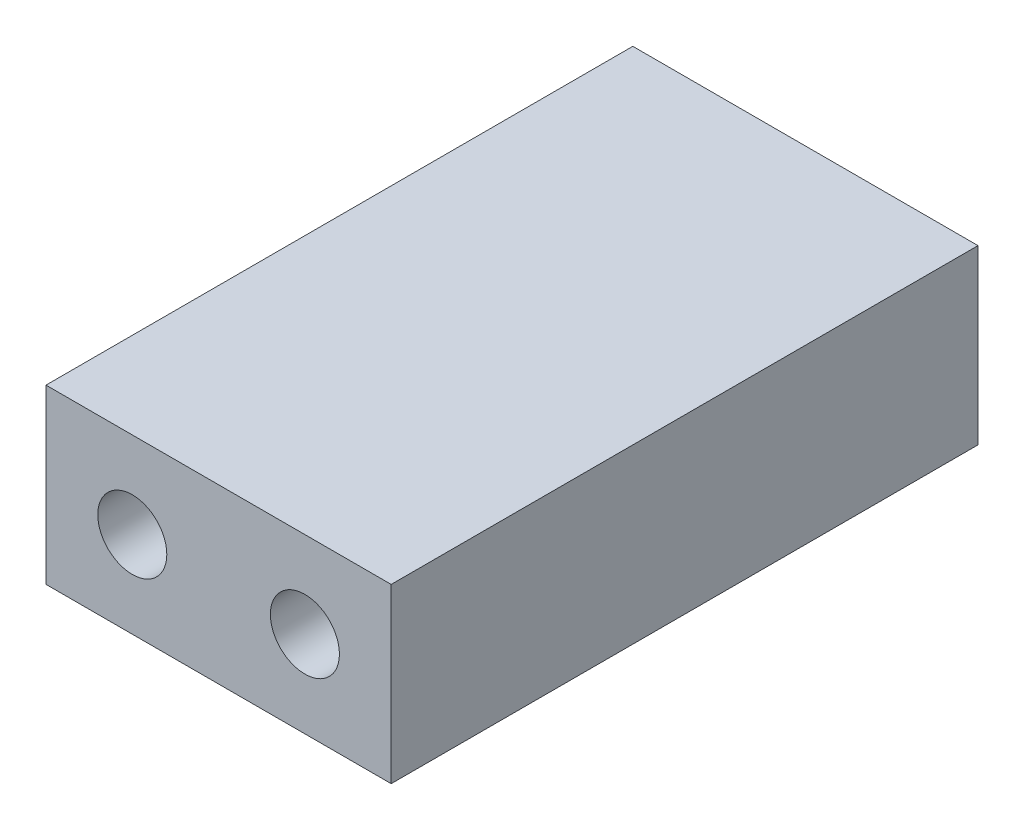
SolidWorks part; units mm, degrees
ref_plane "Front Plane" through (0, 0, 0) normal (0, 0, 1) x (1, 0, 0)
ref_plane "Top Plane" through (0, 0, 0) normal (0, 1, 0) x (1, 0, 0)
ref_plane "Right Plane" through (0, 0, 0) normal (1, 0, 0) x (0, 0, -1)
sketch "Sketch2" plane through (0, 0, 0) normal (0, 0, 1) x (1, 0, 0)
  line L1 (-10, -5) -> (10, -5)
  line L2 (-10, -5) -> (-10, 5)
  line L3 (-10, 5) -> (10, 5)
  line L4 (10, -5) -> (10, 5)
  line L5 (-10, -5) -> (10, 5) construction
  line L6 (-10, 5) -> (10, -5) construction
  point P0 (0, 0)
  dimension "D1" = 10
  dimension "D2" = 20
extrude "Boss-Extrude1" add sketch "Sketch2" along normal blind 34
sketch "Sketch3" plane through (0, 0, 34) normal (0, 0, 1) x (1, 0, 0)
  line L0 (0, 0) -> (-5, 0)
  line L1 (0, 0) -> (5, 0)
  circle A0 centre (-5, 0) radius 2
  circle A1 centre (5, 0) radius 2
  dimension "D2" = 4
  dimension "D4" = 4
  dimension "D1" = 5
  dimension "D3" = 5
extrude "Cut-Extrude1" cut sketch "Sketch3" against normal blind 34
